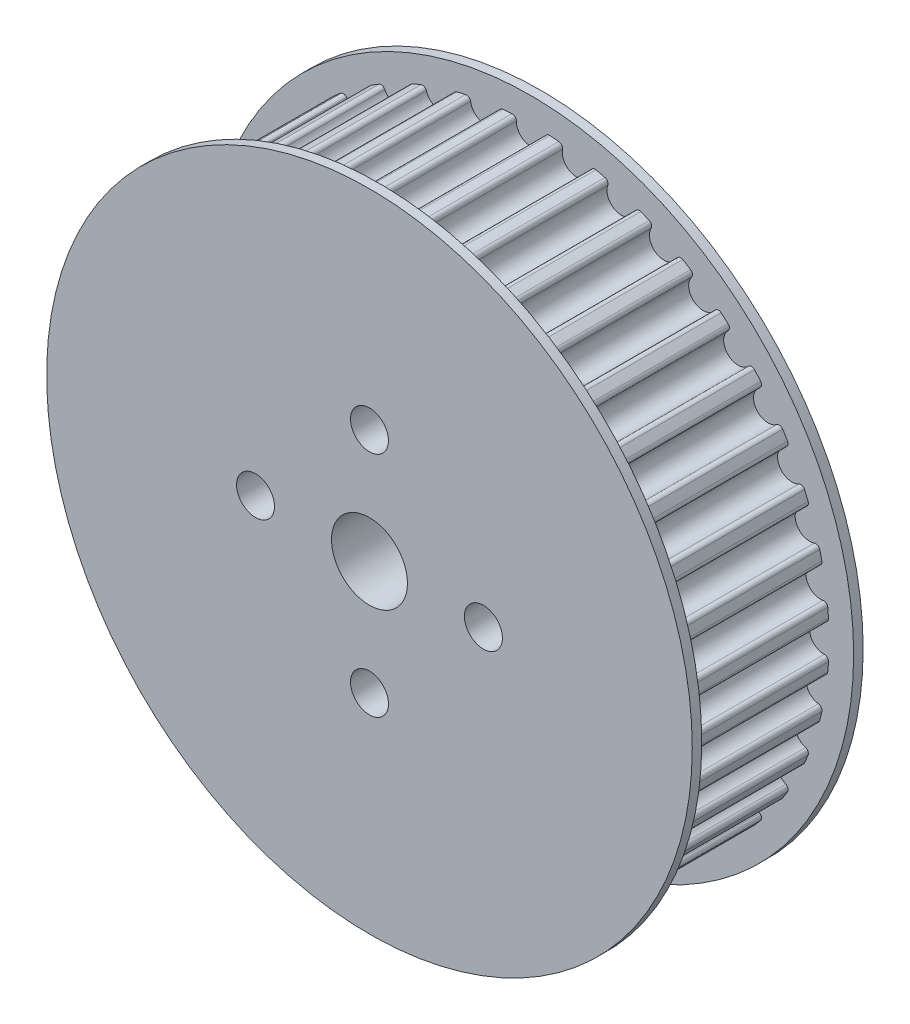
SolidWorks part; units mm, degrees
ref_plane "Front Plane" through (0, 0, 0) normal (0, 0, 1) x (1, 0, 0)
ref_plane "Top Plane" through (0, 0, 0) normal (0, 1, 0) x (1, 0, 0)
ref_plane "Right Plane" through (0, 0, 0) normal (1, 0, 0) x (0, 0, -1)
sketch "Sketch1" plane through (0, 0, 0) normal (0, 0, 1) x (1, 0, 0)
  line L0 (0, 0) -> (0, 52.0511) construction
  line L1 (0, 0) -> (78.6588, 0) construction
  line L2 (0, 0) -> (7.0914, 44.7731) construction
  arc A2 (0, 29.35) -> (1.5246, 30.9088) centre (0, 30.875) ccw
  arc A3 (1.9816, 31.3474) -> (1.5246, 30.9088) centre (1.9545, 30.9183) ccw
  arc A4 (3.3293, 30.7667) -> (4.5914, 28.9887) centre (4.8299, 30.4949) ccw
  arc A5 (3.3293, 30.7667) -> (2.9466, 31.2715) centre (2.9062, 30.8434) ccw
  arc A6 (2.9466, 31.2715) -> (1.9816, 31.3474) centre (0, 0) ccw
  arc A7 (4.5914, 28.9887) -> (6.3411, 30.2897) centre (4.8299, 30.4949) ccw
  arc A8 (6.8611, 30.6515) -> (6.3411, 30.2897) centre (6.7671, 30.2319) ccw
  arc A9 (7.8022, 30.4255) -> (6.8611, 30.6515) centre (0, 0) ccw
  arc A10 (8.1013, 29.8671) -> (7.8022, 30.4255) centre (7.6954, 30.009) ccw
  arc A11 (8.1013, 29.8671) -> (9.0696, 27.9135) centre (9.5409, 29.3639) ccw
  arc A12 (9.0696, 27.9135) -> (11.0013, 28.9248) centre (9.5409, 29.3639) ccw
  arc A13 (11.5715, 29.2008) -> (11.0013, 28.9248) centre (11.4131, 28.8011) ccw
  arc A14 (12.4658, 28.8304) -> (11.5715, 29.2008) centre (0, 0) ccw
  arc A15 (12.6738, 28.2321) -> (12.4658, 28.8304) centre (12.2951, 28.4357) ccw
  arc A16 (12.6738, 28.2321) -> (13.3246, 26.151) centre (14.017, 27.5098) ccw
  arc A17 (13.3246, 26.151) -> (15.3907, 26.8477) centre (14.017, 27.5098) ccw
  arc A18 (15.9971, 27.0311) -> (15.3907, 26.8477) centre (15.7781, 26.6611) ccw
  arc A19 (16.8224, 26.5254) -> (15.9971, 27.0311) centre (0, 0) ccw
  arc A20 (16.9343, 25.9019) -> (16.8224, 26.5254) centre (16.5921, 26.1623) ccw
  arc A21 (16.9343, 25.9019) -> (17.2515, 23.7446) centre (18.1479, 24.9784) ccw
  arc A22 (17.2515, 23.7446) -> (19.4012, 24.1096) centre (18.1479, 24.9784) ccw
  arc A23 (20.0287, 24.1958) -> (19.4012, 24.1096) centre (19.7546, 23.8646) ccw
  arc A24 (20.7647, 23.5672) -> (20.0287, 24.1958) centre (0, 0) ccw
  arc A25 (20.7777, 22.9339) -> (20.7647, 23.5672) centre (20.4805, 23.2446) ccw
  arc A26 (20.7777, 22.9339) -> (20.7536, 20.7536) centre (21.8319, 21.8319) ccw
  arc A27 (20.7536, 20.7536) -> (22.9339, 20.7777) centre (21.8319, 21.8319) ccw
  arc A28 (23.5672, 20.7647) -> (22.9339, 20.7777) centre (23.2446, 20.4805) ccw
  arc A29 (24.1958, 20.0287) -> (23.5672, 20.7647) centre (0, 0) ccw
  arc A30 (24.1096, 19.4012) -> (24.1958, 20.0287) centre (23.8646, 19.7546) ccw
  arc A31 (24.1096, 19.4012) -> (23.7446, 17.2515) centre (24.9784, 18.1479) ccw
  arc A32 (23.7446, 17.2515) -> (25.9019, 16.9343) centre (24.9784, 18.1479) ccw
  arc A33 (26.5254, 16.8224) -> (25.9019, 16.9343) centre (26.1623, 16.5921) ccw
  arc A34 (27.0311, 15.9971) -> (26.5254, 16.8224) centre (0, 0) ccw
  arc A35 (26.8477, 15.3907) -> (27.0311, 15.9971) centre (26.6611, 15.7781) ccw
  arc A36 (26.8477, 15.3907) -> (26.151, 13.3246) centre (27.5098, 14.017) ccw
  arc A37 (26.151, 13.3246) -> (28.2321, 12.6738) centre (27.5098, 14.017) ccw
  arc A38 (28.8304, 12.4658) -> (28.2321, 12.6738) centre (28.4357, 12.2951) ccw
  arc A39 (29.2008, 11.5715) -> (28.8304, 12.4658) centre (0, 0) ccw
  arc A40 (28.9248, 11.0013) -> (29.2008, 11.5715) centre (28.8011, 11.4131) ccw
  arc A41 (28.9248, 11.0013) -> (27.9135, 9.0696) centre (29.3639, 9.5409) ccw
  arc A42 (27.9135, 9.0696) -> (29.8671, 8.1013) centre (29.3639, 9.5409) ccw
  arc A43 (30.4255, 7.8022) -> (29.8671, 8.1013) centre (30.009, 7.6954) ccw
  arc A44 (30.6515, 6.8611) -> (30.4255, 7.8022) centre (0, 0) ccw
  arc A45 (30.2897, 6.3411) -> (30.6515, 6.8611) centre (30.2319, 6.7671) ccw
  arc A46 (30.2897, 6.3411) -> (28.9887, 4.5914) centre (30.4949, 4.8299) ccw
  arc A47 (28.9887, 4.5914) -> (30.7667, 3.3293) centre (30.4949, 4.8299) ccw
  arc A48 (31.2715, 2.9466) -> (30.7667, 3.3293) centre (30.8434, 2.9062) ccw
  arc A49 (31.3474, 1.9816) -> (31.2715, 2.9466) centre (0, 0) ccw
  arc A50 (30.9088, 1.5246) -> (31.3474, 1.9816) centre (30.9183, 1.9545) ccw
  arc A51 (30.9088, 1.5246) -> (29.35, 0) centre (30.875, 0) ccw
  arc A52 (29.35, 0) -> (30.9088, -1.5246) centre (30.875, 0) ccw
  arc A53 (31.3474, -1.9816) -> (30.9088, -1.5246) centre (30.9183, -1.9545) ccw
  arc A54 (31.2715, -2.9466) -> (31.3474, -1.9816) centre (0, 0) ccw
  arc A55 (30.7667, -3.3293) -> (31.2715, -2.9466) centre (30.8434, -2.9062) ccw
  arc A56 (30.7667, -3.3293) -> (28.9887, -4.5914) centre (30.4949, -4.8299) ccw
  arc A57 (28.9887, -4.5914) -> (30.2897, -6.3411) centre (30.4949, -4.8299) ccw
  arc A58 (30.6515, -6.8611) -> (30.2897, -6.3411) centre (30.2319, -6.7671) ccw
  arc A59 (30.4255, -7.8022) -> (30.6515, -6.8611) centre (0, 0) ccw
  arc A60 (29.8671, -8.1013) -> (30.4255, -7.8022) centre (30.009, -7.6954) ccw
  arc A61 (29.8671, -8.1013) -> (27.9135, -9.0696) centre (29.3639, -9.5409) ccw
  arc A62 (27.9135, -9.0696) -> (28.9248, -11.0013) centre (29.3639, -9.5409) ccw
  arc A63 (29.2008, -11.5715) -> (28.9248, -11.0013) centre (28.8011, -11.4131) ccw
  arc A64 (28.8304, -12.4658) -> (29.2008, -11.5715) centre (0, 0) ccw
  arc A65 (28.2321, -12.6738) -> (28.8304, -12.4658) centre (28.4357, -12.2951) ccw
  arc A66 (28.2321, -12.6738) -> (26.151, -13.3246) centre (27.5098, -14.017) ccw
  arc A67 (26.151, -13.3246) -> (26.8477, -15.3907) centre (27.5098, -14.017) ccw
  arc A68 (27.0311, -15.9971) -> (26.8477, -15.3907) centre (26.6611, -15.7781) ccw
  arc A69 (26.5254, -16.8224) -> (27.0311, -15.9971) centre (0, 0) ccw
  arc A70 (25.9019, -16.9343) -> (26.5254, -16.8224) centre (26.1623, -16.5921) ccw
  arc A71 (25.9019, -16.9343) -> (23.7446, -17.2515) centre (24.9784, -18.1479) ccw
  arc A72 (23.7446, -17.2515) -> (24.1096, -19.4012) centre (24.9784, -18.1479) ccw
  arc A73 (24.1958, -20.0287) -> (24.1096, -19.4012) centre (23.8646, -19.7546) ccw
  arc A74 (23.5672, -20.7647) -> (24.1958, -20.0287) centre (0, 0) ccw
  arc A75 (22.9339, -20.7777) -> (23.5672, -20.7647) centre (23.2446, -20.4805) ccw
  arc A76 (22.9339, -20.7777) -> (20.7536, -20.7536) centre (21.8319, -21.8319) ccw
  arc A77 (20.7536, -20.7536) -> (20.7777, -22.9339) centre (21.8319, -21.8319) ccw
  arc A78 (20.7647, -23.5672) -> (20.7777, -22.9339) centre (20.4805, -23.2446) ccw
  arc A79 (20.0287, -24.1958) -> (20.7647, -23.5672) centre (0, 0) ccw
  arc A80 (19.4012, -24.1096) -> (20.0287, -24.1958) centre (19.7546, -23.8646) ccw
  arc A81 (19.4012, -24.1096) -> (17.2515, -23.7446) centre (18.1479, -24.9784) ccw
  arc A82 (17.2515, -23.7446) -> (16.9343, -25.9019) centre (18.1479, -24.9784) ccw
  arc A83 (16.8224, -26.5254) -> (16.9343, -25.9019) centre (16.5921, -26.1623) ccw
  arc A84 (15.9971, -27.0311) -> (16.8224, -26.5254) centre (0, 0) ccw
  arc A85 (15.3907, -26.8477) -> (15.9971, -27.0311) centre (15.7781, -26.6611) ccw
  arc A86 (15.3907, -26.8477) -> (13.3246, -26.151) centre (14.017, -27.5098) ccw
  arc A87 (13.3246, -26.151) -> (12.6738, -28.2321) centre (14.017, -27.5098) ccw
  arc A88 (12.4658, -28.8304) -> (12.6738, -28.2321) centre (12.2951, -28.4357) ccw
  arc A89 (11.5715, -29.2008) -> (12.4658, -28.8304) centre (0, 0) ccw
  arc A90 (11.0013, -28.9248) -> (11.5715, -29.2008) centre (11.4131, -28.8011) ccw
  arc A91 (11.0013, -28.9248) -> (9.0696, -27.9135) centre (9.5409, -29.3639) ccw
  arc A92 (9.0696, -27.9135) -> (8.1013, -29.8671) centre (9.5409, -29.3639) ccw
  arc A93 (7.8022, -30.4255) -> (8.1013, -29.8671) centre (7.6954, -30.009) ccw
  arc A94 (6.8611, -30.6515) -> (7.8022, -30.4255) centre (0, 0) ccw
  arc A95 (6.3411, -30.2897) -> (6.8611, -30.6515) centre (6.7671, -30.2319) ccw
  arc A96 (6.3411, -30.2897) -> (4.5914, -28.9887) centre (4.8299, -30.4949) ccw
  arc A97 (4.5914, -28.9887) -> (3.3293, -30.7667) centre (4.8299, -30.4949) ccw
  arc A98 (2.9466, -31.2715) -> (3.3293, -30.7667) centre (2.9062, -30.8434) ccw
  arc A99 (1.9816, -31.3474) -> (2.9466, -31.2715) centre (0, 0) ccw
  arc A100 (1.5246, -30.9088) -> (1.9816, -31.3474) centre (1.9545, -30.9183) ccw
  arc A101 (1.5246, -30.9088) -> (0, -29.35) centre (0, -30.875) ccw
  arc A102 (0, -29.35) -> (-1.5246, -30.9088) centre (0, -30.875) ccw
  arc A103 (-1.9816, -31.3474) -> (-1.5246, -30.9088) centre (-1.9545, -30.9183) ccw
  arc A104 (-2.9466, -31.2715) -> (-1.9816, -31.3474) centre (0, 0) ccw
  arc A105 (-3.3293, -30.7667) -> (-2.9466, -31.2715) centre (-2.9062, -30.8434) ccw
  arc A106 (-3.3293, -30.7667) -> (-4.5914, -28.9887) centre (-4.8299, -30.4949) ccw
  arc A107 (-4.5914, -28.9887) -> (-6.3411, -30.2897) centre (-4.8299, -30.4949) ccw
  arc A108 (-6.8611, -30.6515) -> (-6.3411, -30.2897) centre (-6.7671, -30.2319) ccw
  arc A109 (-7.8022, -30.4255) -> (-6.8611, -30.6515) centre (0, 0) ccw
  arc A110 (-8.1013, -29.8671) -> (-7.8022, -30.4255) centre (-7.6954, -30.009) ccw
  arc A111 (-8.1013, -29.8671) -> (-9.0696, -27.9135) centre (-9.5409, -29.3639) ccw
  arc A112 (-9.0696, -27.9135) -> (-11.0013, -28.9248) centre (-9.5409, -29.3639) ccw
  arc A113 (-11.5715, -29.2008) -> (-11.0013, -28.9248) centre (-11.4131, -28.8011) ccw
  arc A114 (-12.4658, -28.8304) -> (-11.5715, -29.2008) centre (0, 0) ccw
  arc A115 (-12.6738, -28.2321) -> (-12.4658, -28.8304) centre (-12.2951, -28.4357) ccw
  arc A116 (-12.6738, -28.2321) -> (-13.3246, -26.151) centre (-14.017, -27.5098) ccw
  arc A117 (-13.3246, -26.151) -> (-15.3907, -26.8477) centre (-14.017, -27.5098) ccw
  arc A118 (-15.9971, -27.0311) -> (-15.3907, -26.8477) centre (-15.7781, -26.6611) ccw
  arc A119 (-16.8224, -26.5254) -> (-15.9971, -27.0311) centre (0, 0) ccw
  arc A120 (-16.9343, -25.9019) -> (-16.8224, -26.5254) centre (-16.5921, -26.1623) ccw
  arc A121 (-16.9343, -25.9019) -> (-17.2515, -23.7446) centre (-18.1479, -24.9784) ccw
  arc A122 (-17.2515, -23.7446) -> (-19.4012, -24.1096) centre (-18.1479, -24.9784) ccw
  arc A123 (-20.0287, -24.1958) -> (-19.4012, -24.1096) centre (-19.7546, -23.8646) ccw
  arc A124 (-20.7647, -23.5672) -> (-20.0287, -24.1958) centre (0, 0) ccw
  arc A125 (-20.7777, -22.9339) -> (-20.7647, -23.5672) centre (-20.4805, -23.2446) ccw
  arc A126 (-20.7777, -22.9339) -> (-20.7536, -20.7536) centre (-21.8319, -21.8319) ccw
  arc A127 (-20.7536, -20.7536) -> (-22.9339, -20.7777) centre (-21.8319, -21.8319) ccw
  arc A128 (-23.5672, -20.7647) -> (-22.9339, -20.7777) centre (-23.2446, -20.4805) ccw
  arc A129 (-24.1958, -20.0287) -> (-23.5672, -20.7647) centre (0, 0) ccw
  arc A130 (-24.1096, -19.4012) -> (-24.1958, -20.0287) centre (-23.8646, -19.7546) ccw
  arc A131 (-24.1096, -19.4012) -> (-23.7446, -17.2515) centre (-24.9784, -18.1479) ccw
  arc A132 (-23.7446, -17.2515) -> (-25.9019, -16.9343) centre (-24.9784, -18.1479) ccw
  arc A133 (-26.5254, -16.8224) -> (-25.9019, -16.9343) centre (-26.1623, -16.5921) ccw
  arc A134 (-27.0311, -15.9971) -> (-26.5254, -16.8224) centre (0, 0) ccw
  arc A135 (-26.8477, -15.3907) -> (-27.0311, -15.9971) centre (-26.6611, -15.7781) ccw
  arc A136 (-26.8477, -15.3907) -> (-26.151, -13.3246) centre (-27.5098, -14.017) ccw
  arc A137 (-26.151, -13.3246) -> (-28.2321, -12.6738) centre (-27.5098, -14.017) ccw
  arc A138 (-28.8304, -12.4658) -> (-28.2321, -12.6738) centre (-28.4357, -12.2951) ccw
  arc A139 (-29.2008, -11.5715) -> (-28.8304, -12.4658) centre (0, 0) ccw
  arc A140 (-28.9248, -11.0013) -> (-29.2008, -11.5715) centre (-28.8011, -11.4131) ccw
  arc A141 (-28.9248, -11.0013) -> (-27.9135, -9.0696) centre (-29.3639, -9.5409) ccw
  arc A142 (-27.9135, -9.0696) -> (-29.8671, -8.1013) centre (-29.3639, -9.5409) ccw
  arc A143 (-30.4255, -7.8022) -> (-29.8671, -8.1013) centre (-30.009, -7.6954) ccw
  arc A144 (-30.6515, -6.8611) -> (-30.4255, -7.8022) centre (0, 0) ccw
  arc A145 (-30.2897, -6.3411) -> (-30.6515, -6.8611) centre (-30.2319, -6.7671) ccw
  arc A146 (-30.2897, -6.3411) -> (-28.9887, -4.5914) centre (-30.4949, -4.8299) ccw
  arc A147 (-28.9887, -4.5914) -> (-30.7667, -3.3293) centre (-30.4949, -4.8299) ccw
  arc A148 (-31.2715, -2.9466) -> (-30.7667, -3.3293) centre (-30.8434, -2.9062) ccw
  arc A149 (-31.3474, -1.9816) -> (-31.2715, -2.9466) centre (0, 0) ccw
  arc A150 (-30.9088, -1.5246) -> (-31.3474, -1.9816) centre (-30.9183, -1.9545) ccw
  arc A151 (-30.9088, -1.5246) -> (-29.35, 0) centre (-30.875, 0) ccw
  arc A152 (-29.35, 0) -> (-30.9088, 1.5246) centre (-30.875, 0) ccw
  arc A153 (-31.3474, 1.9816) -> (-30.9088, 1.5246) centre (-30.9183, 1.9545) ccw
  arc A154 (-31.2715, 2.9466) -> (-31.3474, 1.9816) centre (0, 0) ccw
  arc A155 (-30.7667, 3.3293) -> (-31.2715, 2.9466) centre (-30.8434, 2.9062) ccw
  arc A156 (-30.7667, 3.3293) -> (-28.9887, 4.5914) centre (-30.4949, 4.8299) ccw
  arc A157 (-28.9887, 4.5914) -> (-30.2897, 6.3411) centre (-30.4949, 4.8299) ccw
  arc A158 (-30.6515, 6.8611) -> (-30.2897, 6.3411) centre (-30.2319, 6.7671) ccw
  arc A159 (-30.4255, 7.8022) -> (-30.6515, 6.8611) centre (0, 0) ccw
  arc A160 (-29.8671, 8.1013) -> (-30.4255, 7.8022) centre (-30.009, 7.6954) ccw
  arc A161 (-29.8671, 8.1013) -> (-27.9135, 9.0696) centre (-29.3639, 9.5409) ccw
  arc A162 (-27.9135, 9.0696) -> (-28.9248, 11.0013) centre (-29.3639, 9.5409) ccw
  arc A163 (-29.2008, 11.5715) -> (-28.9248, 11.0013) centre (-28.8011, 11.4131) ccw
  arc A164 (-28.8304, 12.4658) -> (-29.2008, 11.5715) centre (0, 0) ccw
  arc A165 (-28.2321, 12.6738) -> (-28.8304, 12.4658) centre (-28.4357, 12.2951) ccw
  arc A166 (-28.2321, 12.6738) -> (-26.151, 13.3246) centre (-27.5098, 14.017) ccw
  arc A167 (-26.151, 13.3246) -> (-26.8477, 15.3907) centre (-27.5098, 14.017) ccw
  arc A168 (-27.0311, 15.9971) -> (-26.8477, 15.3907) centre (-26.6611, 15.7781) ccw
  arc A169 (-26.5254, 16.8224) -> (-27.0311, 15.9971) centre (0, 0) ccw
  arc A170 (-25.9019, 16.9343) -> (-26.5254, 16.8224) centre (-26.1623, 16.5921) ccw
  arc A171 (-25.9019, 16.9343) -> (-23.7446, 17.2515) centre (-24.9784, 18.1479) ccw
  arc A172 (-23.7446, 17.2515) -> (-24.1096, 19.4012) centre (-24.9784, 18.1479) ccw
  arc A173 (-24.1958, 20.0287) -> (-24.1096, 19.4012) centre (-23.8646, 19.7546) ccw
  arc A174 (-23.5672, 20.7647) -> (-24.1958, 20.0287) centre (0, 0) ccw
  arc A175 (-22.9339, 20.7777) -> (-23.5672, 20.7647) centre (-23.2446, 20.4805) ccw
  arc A176 (-22.9339, 20.7777) -> (-20.7536, 20.7536) centre (-21.8319, 21.8319) ccw
  arc A177 (-20.7536, 20.7536) -> (-20.7777, 22.9339) centre (-21.8319, 21.8319) ccw
  arc A178 (-20.7647, 23.5672) -> (-20.7777, 22.9339) centre (-20.4805, 23.2446) ccw
  arc A179 (-20.0287, 24.1958) -> (-20.7647, 23.5672) centre (0, 0) ccw
  arc A180 (-19.4012, 24.1096) -> (-20.0287, 24.1958) centre (-19.7546, 23.8646) ccw
  arc A181 (-19.4012, 24.1096) -> (-17.2515, 23.7446) centre (-18.1479, 24.9784) ccw
  arc A182 (-17.2515, 23.7446) -> (-16.9343, 25.9019) centre (-18.1479, 24.9784) ccw
  arc A183 (-16.8224, 26.5254) -> (-16.9343, 25.9019) centre (-16.5921, 26.1623) ccw
  arc A184 (-15.9971, 27.0311) -> (-16.8224, 26.5254) centre (0, 0) ccw
  arc A185 (-15.3907, 26.8477) -> (-15.9971, 27.0311) centre (-15.7781, 26.6611) ccw
  arc A186 (-15.3907, 26.8477) -> (-13.3246, 26.151) centre (-14.017, 27.5098) ccw
  arc A187 (-13.3246, 26.151) -> (-12.6738, 28.2321) centre (-14.017, 27.5098) ccw
  arc A188 (-12.4658, 28.8304) -> (-12.6738, 28.2321) centre (-12.2951, 28.4357) ccw
  arc A189 (-11.5715, 29.2008) -> (-12.4658, 28.8304) centre (0, 0) ccw
  arc A190 (-11.0013, 28.9248) -> (-11.5715, 29.2008) centre (-11.4131, 28.8011) ccw
  arc A191 (-11.0013, 28.9248) -> (-9.0696, 27.9135) centre (-9.5409, 29.3639) ccw
  arc A192 (-9.0696, 27.9135) -> (-8.1013, 29.8671) centre (-9.5409, 29.3639) ccw
  arc A193 (-7.8022, 30.4255) -> (-8.1013, 29.8671) centre (-7.6954, 30.009) ccw
  arc A194 (-6.8611, 30.6515) -> (-7.8022, 30.4255) centre (0, 0) ccw
  arc A195 (-6.3411, 30.2897) -> (-6.8611, 30.6515) centre (-6.7671, 30.2319) ccw
  arc A196 (-6.3411, 30.2897) -> (-4.5914, 28.9887) centre (-4.8299, 30.4949) ccw
  arc A197 (-4.5914, 28.9887) -> (-3.3293, 30.7667) centre (-4.8299, 30.4949) ccw
  arc A198 (-2.9466, 31.2715) -> (-3.3293, 30.7667) centre (-2.9062, 30.8434) ccw
  arc A199 (-1.9816, 31.3474) -> (-2.9466, 31.2715) centre (0, 0) ccw
  arc A200 (-1.5246, 30.9088) -> (-1.9816, 31.3474) centre (-1.9545, 30.9183) ccw
  arc A201 (-1.5246, 30.9088) -> (0, 29.35) centre (0, 30.875) ccw
  point P409 (0, 0)
  dimension "D1" = 40
  dimension "D3" = 3.05
  dimension "D4" = 0.86
  dimension "D6" = 3.05
  dimension "D7" = 0.86
extrude "Boss-Extrude1" add sketch "Sketch1" along normal blind 16
sketch "Sketch2" plane through (0, 0, 16) normal (0, 0, 1) x (1, 0, 0)
  circle A0 centre (0, 0) radius 34
  dimension "D1" = 68
extrude "Boss-Extrude2" add sketch "Sketch2" along normal blind 1
ref_plane "Plane1" through (0, 0, 8) normal (0, 0, -1) x (-1, 0, 0)
mirror "Mirror1" about plane through (0, 0, 8) normal (0, 0, -1) of "Boss-Extrude2"
sketch "Sketch3" plane through (0, 0, 17) normal (0, 0, 1) x (1, 0, 0)
  circle A0 centre (0, 0) radius 4
  circle A1 centre (12, 0) radius 2
  circle A2 centre (0, -12) radius 2
  circle A3 centre (-12, 0) radius 2
  circle A4 centre (0, 12) radius 2
  point P14 (0, 0)
  dimension "D1" = 8
  dimension "D3" = 4
  dimension "D2" = 12
  dimension "D4" = 4
extrude "Cut-Extrude1" cut sketch "Sketch3" against normal through all
